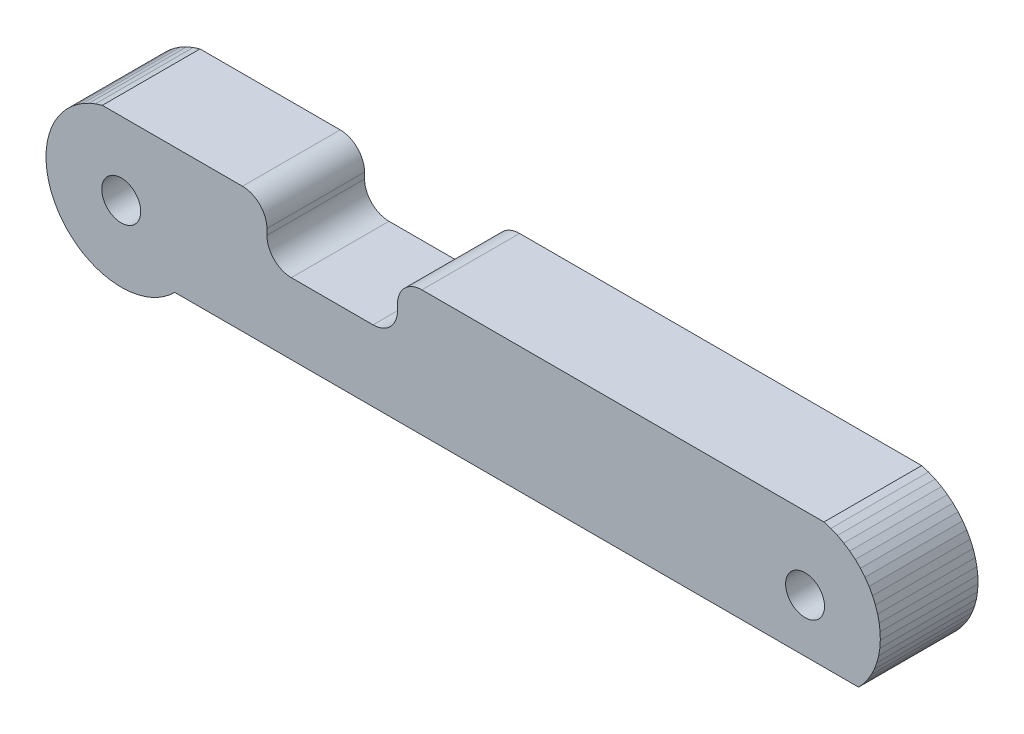
SolidWorks part; units mm, degrees
ref_plane "Front Plane" through (0, 0, 0) normal (0, 0, 1) x (1, 0, 0)
ref_plane "Top Plane" through (0, 0, 0) normal (0, 1, 0) x (1, 0, 0)
ref_plane "Right Plane" through (0, 0, 0) normal (1, 0, 0) x (0, 0, -1)
ref_plane "Plane1" through (0, 0, 0) normal (0, 0, -1) x (-1, 0, 0)
sketch "Sketch1" plane through (0, 0, 0) normal (0, 0, -1) x (-1, 0, 0)
  line L0 (150.2249, 11.5257) -> (149.0942, 12.4373)
  line L1 (149.0942, 12.4373) -> (147.8827, 13.2384)
  line L2 (147.8827, 13.2384) -> (146.6011, 13.9218)
  line L3 (146.6011, 13.9218) -> (145.2609, 14.4815)
  line L4 (145.2609, 14.4815) -> (143.874, 14.9125)
  line L5 (143.874, 14.9125) -> (-3.874, 14.9125)
  line L6 (-3.874, 14.9125) -> (-5.2758, 14.4761)
  line L7 (-5.2758, 14.4761) -> (-6.6297, 13.9082)
  line L8 (-6.6297, 13.9082) -> (-7.9234, 13.2141)
  line L9 (-7.9234, 13.2141) -> (-9.1451, 12.3999)
  line L10 (-9.1451, 12.3999) -> (-10.2838, 11.4732)
  line L11 (-10.2838, 11.4732) -> (-11.3292, 10.4423)
  line L12 (-11.3292, 10.4423) -> (-12.2716, 9.3165)
  line L13 (-12.2716, 9.3165) -> (-13.1027, 8.1062)
  line L14 (-13.1027, 8.1062) -> (-13.8148, 6.8223)
  line L15 (-13.8148, 6.8223) -> (-14.4014, 5.4764)
  line L16 (-14.4014, 5.4764) -> (-14.8573, 4.0808)
  line L17 (-14.8573, 4.0808) -> (-15.1782, 2.6482)
  line L18 (-15.1782, 2.6482) -> (-15.3614, 1.1915)
  line L19 (-15.3614, 1.1915) -> (-15.405, -0.2761)
  line L20 (-15.405, -0.2761) -> (-15.3088, -1.7411)
  line L21 (-15.3088, -1.7411) -> (-15.0736, -3.1903)
  line L22 (-15.0736, -3.1903) -> (-14.7015, -4.6105)
  line L23 (-14.7015, -4.6105) -> (-14.1959, -5.9889)
  line L24 (-14.1959, -5.9889) -> (-13.5614, -7.3129)
  line L25 (-13.5614, -7.3129) -> (-12.8038, -8.5705)
  line L26 (-12.8038, -8.5705) -> (-11.93, -9.7502)
  line L27 (-11.93, -9.7502) -> (-10.9478, -10.8415)
  line L28 (-10.9478, -10.8415) -> (129.0522, -10.8415)
  line L29 (129.0522, -10.8415) -> (130.1217, -11.8242)
  line L30 (130.1217, -11.8242) -> (131.279, -12.7018)
  line L31 (131.279, -12.7018) -> (132.5137, -13.4665)
  line L32 (132.5137, -13.4665) -> (133.815, -14.1116)
  line L33 (133.815, -14.1116) -> (135.1712, -14.6313)
  line L34 (135.1712, -14.6313) -> (136.5704, -15.0209)
  line L35 (136.5704, -15.0209) -> (138, -15.2771)
  line L36 (138, -15.2771) -> (139.4474, -15.3976)
  line L37 (139.4474, -15.3976) -> (140.8997, -15.3812)
  line L38 (140.8997, -15.3812) -> (142.344, -15.2282)
  line L39 (142.344, -15.2282) -> (143.7675, -14.9398)
  line L40 (143.7675, -14.9398) -> (145.1575, -14.5187)
  line L41 (145.1575, -14.5187) -> (146.5016, -13.9685)
  line L42 (146.5016, -13.9685) -> (147.788, -13.2943)
  line L43 (147.788, -13.2943) -> (149.0052, -12.5019)
  line L44 (149.0052, -12.5019) -> (150.1424, -11.5984)
  line L45 (150.1424, -11.5984) -> (151.1894, -10.5919)
  line L46 (151.1894, -10.5919) -> (152.1371, -9.4912)
  line L47 (152.1371, -9.4912) -> (152.9768, -8.3062)
  line L48 (152.9768, -8.3062) -> (153.7013, -7.0474)
  line L49 (153.7013, -7.0474) -> (154.304, -5.726)
  line L50 (154.304, -5.726) -> (154.7796, -4.3536)
  line L51 (154.7796, -4.3536) -> (155.1239, -2.9426)
  line L52 (155.1239, -2.9426) -> (155.3338, -1.5055)
  line L53 (155.3338, -1.5055) -> (155.4074, -0.055)
  line L54 (155.4074, -0.055) -> (155.3441, 1.396)
  line L55 (155.3441, 1.396) -> (155.1445, 2.8347)
  line L56 (155.1445, 2.8347) -> (154.8103, 4.2481)
  line L57 (154.8103, 4.2481) -> (154.3445, 5.6237)
  line L58 (154.3445, 5.6237) -> (153.7512, 6.9494)
  line L59 (153.7512, 6.9494) -> (153.0358, 8.2134)
  line L60 (153.0358, 8.2134) -> (152.2045, 9.4043)
  line L61 (152.2045, 9.4043) -> (151.2647, 10.5117)
  line L62 (151.2647, 10.5117) -> (150.2249, 11.5257)
extrude "Boss-Extrude1" add sketch "Sketch1" against normal blind 20
sketch "Sketch2" plane through (0, 0, 20) normal (0, 0, 1) x (1, 0, 0)
  line L0 (3.7299, 1.445) -> (3.4009, 2.1057)
  line L1 (3.4009, 2.1057) -> (2.956, 2.6948)
  line L2 (2.956, 2.6948) -> (2.4105, 3.1921)
  line L3 (2.4105, 3.1921) -> (1.783, 3.5807)
  line L4 (1.783, 3.5807) -> (1.0947, 3.8473)
  line L5 (1.0947, 3.8473) -> (0.3691, 3.9829)
  line L6 (0.3691, 3.9829) -> (-0.3691, 3.9829)
  line L7 (-0.3691, 3.9829) -> (-1.0947, 3.8473)
  line L8 (-1.0947, 3.8473) -> (-1.783, 3.5807)
  line L9 (-1.783, 3.5807) -> (-2.4105, 3.1921)
  line L10 (-2.4105, 3.1921) -> (-2.956, 2.6948)
  line L11 (-2.956, 2.6948) -> (-3.4009, 2.1057)
  line L12 (-3.4009, 2.1057) -> (-3.7299, 1.445)
  line L13 (-3.7299, 1.445) -> (-3.9319, 0.735)
  line L14 (-3.9319, 0.735) -> (-4, 0)
  line L15 (-4, 0) -> (-3.9319, -0.735)
  line L16 (-3.9319, -0.735) -> (-3.7299, -1.445)
  line L17 (-3.7299, -1.445) -> (-3.4009, -2.1057)
  line L18 (-3.4009, -2.1057) -> (-2.956, -2.6948)
  line L19 (-2.956, -2.6948) -> (-2.4105, -3.1921)
  line L20 (-2.4105, -3.1921) -> (-1.783, -3.5807)
  line L21 (-1.783, -3.5807) -> (-1.0947, -3.8473)
  line L22 (-1.0947, -3.8473) -> (-0.3691, -3.9829)
  line L23 (-0.3691, -3.9829) -> (0.3691, -3.9829)
  line L24 (0.3691, -3.9829) -> (1.0947, -3.8473)
  line L25 (1.0947, -3.8473) -> (1.783, -3.5807)
  line L26 (1.783, -3.5807) -> (2.4105, -3.1921)
  line L27 (2.4105, -3.1921) -> (2.956, -2.6948)
  line L28 (2.956, -2.6948) -> (3.4009, -2.1057)
  line L29 (3.4009, -2.1057) -> (3.7299, -1.445)
  line L30 (3.7299, -1.445) -> (3.9319, -0.735)
  line L31 (3.9319, -0.735) -> (4, 0)
  line L32 (4, 0) -> (3.9319, 0.735)
  line L33 (3.9319, 0.735) -> (3.7299, 1.445)
extrude "Cut-Extrude1" cut sketch "Sketch2" against normal through all
sketch "Sketch3" plane through (0, 0, 20) normal (0, 0, 1) x (1, 0, 0)
  line L0 (-139.6309, 3.9829) -> (-140.3691, 3.9829)
  line L1 (-140.3691, 3.9829) -> (-141.0947, 3.8473)
  line L2 (-141.0947, 3.8473) -> (-141.783, 3.5807)
  line L3 (-141.783, 3.5807) -> (-142.4105, 3.1921)
  line L4 (-142.4105, 3.1921) -> (-142.956, 2.6948)
  line L5 (-142.956, 2.6948) -> (-143.4009, 2.1057)
  line L6 (-143.4009, 2.1057) -> (-143.7299, 1.445)
  line L7 (-143.7299, 1.445) -> (-143.9319, 0.735)
  line L8 (-143.9319, 0.735) -> (-144, 0)
  line L9 (-144, 0) -> (-143.9319, -0.735)
  line L10 (-143.9319, -0.735) -> (-143.7299, -1.445)
  line L11 (-143.7299, -1.445) -> (-143.4009, -2.1057)
  line L12 (-143.4009, -2.1057) -> (-142.956, -2.6948)
  line L13 (-142.956, -2.6948) -> (-142.4105, -3.1921)
  line L14 (-142.4105, -3.1921) -> (-141.783, -3.5807)
  line L15 (-141.783, -3.5807) -> (-141.0947, -3.8473)
  line L16 (-141.0947, -3.8473) -> (-140.3691, -3.9829)
  line L17 (-140.3691, -3.9829) -> (-139.6309, -3.9829)
  line L18 (-139.6309, -3.9829) -> (-138.9053, -3.8473)
  line L19 (-138.9053, -3.8473) -> (-138.217, -3.5807)
  line L20 (-138.217, -3.5807) -> (-137.5895, -3.1921)
  line L21 (-137.5895, -3.1921) -> (-137.044, -2.6948)
  line L22 (-137.044, -2.6948) -> (-136.5991, -2.1057)
  line L23 (-136.5991, -2.1057) -> (-136.2701, -1.445)
  line L24 (-136.2701, -1.445) -> (-136.0681, -0.735)
  line L25 (-136.0681, -0.735) -> (-136, 0)
  line L26 (-136, 0) -> (-136.0681, 0.735)
  line L27 (-136.0681, 0.735) -> (-136.2701, 1.445)
  line L28 (-136.2701, 1.445) -> (-136.5991, 2.1057)
  line L29 (-136.5991, 2.1057) -> (-137.044, 2.6948)
  line L30 (-137.044, 2.6948) -> (-137.5895, 3.1921)
  line L31 (-137.5895, 3.1921) -> (-138.217, 3.5807)
  line L32 (-138.217, 3.5807) -> (-138.9053, 3.8473)
  line L33 (-138.9053, 3.8473) -> (-139.6309, 3.9829)
extrude "Cut-Extrude2" cut sketch "Sketch3" against normal through all
sketch "Sketch4" plane through (0, -10.8415, 0) normal (0, -1, 0) x (1, 0, 0)
  line L0 (1.3314, 10.725) -> (1.1865, 10.3753)
  line L1 (1.1865, 10.3753) -> (1.1371, 10)
  line L2 (1.1371, 10) -> (1.1865, 9.6247)
  line L3 (1.1865, 9.6247) -> (1.3314, 9.275)
  line L4 (1.3314, 9.275) -> (1.5618, 8.9747)
  line L5 (1.5618, 8.9747) -> (1.8621, 8.7443)
  line L6 (1.8621, 8.7443) -> (2.2118, 8.5994)
  line L7 (2.2118, 8.5994) -> (2.5871, 8.55)
  line L8 (2.5871, 8.55) -> (2.9624, 8.5994)
  line L9 (2.9624, 8.5994) -> (3.3121, 8.7443)
  line L10 (3.3121, 8.7443) -> (3.6124, 8.9747)
  line L11 (3.6124, 8.9747) -> (3.8428, 9.275)
  line L12 (3.8428, 9.275) -> (3.9877, 9.6247)
  line L13 (3.9877, 9.6247) -> (4.0371, 10)
  line L14 (4.0371, 10) -> (3.9877, 10.3753)
  line L15 (3.9877, 10.3753) -> (3.8428, 10.725)
  line L16 (3.8428, 10.725) -> (3.6124, 11.0253)
  line L17 (3.6124, 11.0253) -> (3.3121, 11.2557)
  line L18 (3.3121, 11.2557) -> (2.9624, 11.4006)
  line L19 (2.9624, 11.4006) -> (2.5871, 11.45)
  line L20 (2.5871, 11.45) -> (2.2118, 11.4006)
  line L21 (2.2118, 11.4006) -> (1.8621, 11.2557)
  line L22 (1.8621, 11.2557) -> (1.5618, 11.0253)
  line L23 (1.5618, 11.0253) -> (1.3314, 10.725)
sketch "Sketch5" plane through (0, -10.8415, 0) normal (0, -1, 0) x (1, 0, 0)
  line L0 (-42.0428, 10.725) -> (-42.1877, 10.3753)
  line L1 (-42.1877, 10.3753) -> (-42.2371, 10)
  line L2 (-42.2371, 10) -> (-42.1877, 9.6247)
  line L3 (-42.1877, 9.6247) -> (-42.0428, 9.275)
  line L4 (-42.0428, 9.275) -> (-41.8124, 8.9747)
  line L5 (-41.8124, 8.9747) -> (-41.5121, 8.7443)
  line L6 (-41.5121, 8.7443) -> (-41.1624, 8.5994)
  line L7 (-41.1624, 8.5994) -> (-40.7871, 8.55)
  line L8 (-40.7871, 8.55) -> (-40.4118, 8.5994)
  line L9 (-40.4118, 8.5994) -> (-40.0621, 8.7443)
  line L10 (-40.0621, 8.7443) -> (-39.7618, 8.9747)
  line L11 (-39.7618, 8.9747) -> (-39.5314, 9.275)
  line L12 (-39.5314, 9.275) -> (-39.3865, 9.6247)
  line L13 (-39.3865, 9.6247) -> (-39.3371, 10)
  line L14 (-39.3371, 10) -> (-39.3865, 10.3753)
  line L15 (-39.3865, 10.3753) -> (-39.5314, 10.725)
  line L16 (-39.5314, 10.725) -> (-39.7618, 11.0253)
  line L17 (-39.7618, 11.0253) -> (-40.0621, 11.2557)
  line L18 (-40.0621, 11.2557) -> (-40.4118, 11.4006)
  line L19 (-40.4118, 11.4006) -> (-40.7871, 11.45)
  line L20 (-40.7871, 11.45) -> (-41.1624, 11.4006)
  line L21 (-41.1624, 11.4006) -> (-41.5121, 11.2557)
  line L22 (-41.5121, 11.2557) -> (-41.8124, 11.0253)
  line L23 (-41.8124, 11.0253) -> (-42.0428, 10.725)
ref_plane "Plane2" through (0, 0, -10) normal (0, 0, -1) x (-1, 0, 0)
sketch "Sketch6" plane through (0, 0, -10) normal (0, 0, -1) x (-1, 0, 0)
  line L126 (151.2647, 10.6737) -> (150.2249, 11.6877)
  line L127 (150.2249, 11.6877) -> (149.0942, 12.5993)
  line L128 (149.0942, 12.5993) -> (147.8827, 13.4004)
  line L129 (147.8827, 13.4004) -> (146.6011, 14.0838)
  line L130 (146.6011, 14.0838) -> (145.2609, 14.6435)
  line L131 (145.2609, 14.6435) -> (143.874, 15.0745)
  line L132 (143.874, 15.0745) -> (-3.874, 15.0745)
  line L133 (-3.874, 15.0745) -> (-5.2758, 14.6381)
  line L134 (-5.2758, 14.6381) -> (-6.6297, 14.0702)
  line L135 (-6.6297, 14.0702) -> (-7.9234, 13.376)
  line L136 (-7.9234, 13.376) -> (-9.1451, 12.5619)
  line L137 (-9.1451, 12.5619) -> (-10.2838, 11.6352)
  line L138 (-10.2838, 11.6352) -> (-11.3292, 10.6043)
  line L139 (-11.3292, 10.6043) -> (-12.2716, 9.4785)
  line L140 (-12.2716, 9.4785) -> (-13.1027, 8.2682)
  line L141 (-13.1027, 8.2682) -> (-13.8148, 6.9843)
  line L142 (-13.8148, 6.9843) -> (-14.4014, 5.6384)
  line L143 (-14.4014, 5.6384) -> (-14.8573, 4.2428)
  line L144 (-14.8573, 4.2428) -> (-15.1782, 2.8101)
  line L145 (-15.1782, 2.8101) -> (-15.3614, 1.3534)
  line L146 (-15.3614, 1.3534) -> (-15.405, -0.1141)
  line L147 (-15.405, -0.1141) -> (-15.3088, -1.5791)
  line L148 (-15.3088, -1.5791) -> (-15.0736, -3.0283)
  line L149 (-15.0736, -3.0283) -> (-14.7015, -4.4485)
  line L150 (-14.7015, -4.4485) -> (-14.1959, -5.8269)
  line L151 (-14.1959, -5.8269) -> (-13.5614, -7.1509)
  line L152 (-13.5614, -7.1509) -> (-12.8038, -8.4085)
  line L153 (-12.8038, -8.4085) -> (-11.93, -9.5882)
  line L154 (-11.93, -9.5882) -> (-10.9478, -10.6795)
  line L155 (-10.9478, -10.6795) -> (129.0522, -10.6795)
  line L156 (129.0522, -10.6795) -> (130.1217, -11.6622)
  line L157 (130.1217, -11.6622) -> (131.279, -12.5398)
  line L158 (131.279, -12.5398) -> (132.5137, -13.3045)
  line L159 (132.5137, -13.3045) -> (133.815, -13.9496)
  line L160 (133.815, -13.9496) -> (135.1712, -14.4693)
  line L161 (135.1712, -14.4693) -> (136.5704, -14.859)
  line L162 (136.5704, -14.859) -> (138, -15.1152)
  line L163 (138, -15.1152) -> (139.4474, -15.2356)
  line L164 (139.4474, -15.2356) -> (140.8997, -15.2192)
  line L165 (140.8997, -15.2192) -> (142.344, -15.0662)
  line L166 (142.344, -15.0662) -> (143.7675, -14.7778)
  line L167 (143.7675, -14.7778) -> (145.1575, -14.3567)
  line L168 (145.1575, -14.3567) -> (146.5016, -13.8065)
  line L169 (146.5016, -13.8065) -> (147.788, -13.1323)
  line L170 (147.788, -13.1323) -> (149.0052, -12.3399)
  line L171 (149.0052, -12.3399) -> (150.1424, -11.4364)
  line L172 (150.1424, -11.4364) -> (151.1894, -10.4299)
  line L173 (151.1894, -10.4299) -> (152.1371, -9.3292)
  line L174 (152.1371, -9.3292) -> (152.9768, -8.1442)
  line L175 (152.9768, -8.1442) -> (153.7013, -6.8854)
  line L176 (153.7013, -6.8854) -> (154.304, -5.564)
  line L177 (154.304, -5.564) -> (154.7796, -4.1917)
  line L178 (154.7796, -4.1917) -> (155.1239, -2.7807)
  line L179 (155.1239, -2.7807) -> (155.3338, -1.3435)
  line L180 (155.3338, -1.3435) -> (155.4074, 0.107)
  line L181 (155.4074, 0.107) -> (155.3441, 1.558)
  line L182 (155.3441, 1.558) -> (155.1445, 2.9966)
  line L183 (155.1445, 2.9966) -> (154.8103, 4.4101)
  line L184 (154.8103, 4.4101) -> (154.3445, 5.7857)
  line L185 (154.3445, 5.7857) -> (153.7512, 7.1114)
  line L186 (153.7512, 7.1114) -> (153.0358, 8.3754)
  line L187 (153.0358, 8.3754) -> (152.2045, 9.5663)
  line L188 (152.2045, 9.5663) -> (151.2647, 10.6737)
  circle A0 centre (0, 0) radius 3.9829
  circle A1 centre (140.0068, -0.0089) radius 3.9905
ref_plane "Plane3" through (0, 0, 20) normal (0, 0, 1) x (1, 0, 0)
sketch "Sketch7" plane through (0, 0, 20) normal (0, 0, 1) x (1, 0, 0)
  line L1 (-147.5796, 5.778) -> (-131.7543, 5.778)
  line L2 (-147.5796, 5.778) -> (-147.5796, -6.435)
  line L3 (-147.5796, -6.435) -> (-131.7543, -6.435)
  line L4 (-131.7543, 5.778) -> (-131.7543, -6.435)
  line L5 (-5.0827, 4.2322) -> (5.4063, 4.2322)
  line L6 (-5.0827, 4.2322) -> (-5.0827, -4.2285)
  line L7 (-5.0827, -4.2285) -> (5.4063, -4.2285)
  line L8 (5.4063, 4.2322) -> (5.4063, -4.2285)
extrude "Boss-Extrude5" add sketch "Sketch7" against normal blind 20
extrude "Cut-Extrude8" cut sketch "Sketch6" against normal blind 40 contours A0 | A1
sketch "Sketch8" plane through (0, 0, 20) normal (0, 0, 1) x (1, 0, 0)
  line L0 (-143.874, 14.9125) -> (3.874, 14.9125) construction
  line L1 (-83.4461, 14.9125) -> (-110.1805, 14.9125)
  line L2 (-83.4461, 14.9125) -> (-83.4461, 3.7017)
  line L3 (-83.4461, 3.7017) -> (-110.1805, 3.7017)
  line L4 (-110.1805, 14.9125) -> (-110.1805, 3.7017)
  line L5 (-83.5177, 3.5341) -> (-83.1429, 63.1605) construction
extrude "Cut-Extrude9" cut sketch "Sketch8" against normal blind 30
fillet "Fillet1" radius 5 2 edges at (-83.4461, 3.7017, 10) (-110.1805, 3.7017, 10)
fillet "Fillet2" radius 5 2 edges at (-83.4461, 14.9125, 10) (-110.1805, 14.9125, 10)
sketch "Sketch9" plane through (0, 2.5492, 0) normal (0, 0, -1) x (-1, 0, 0)
  line L0 (6.3747, 5.0663) -> (6.3747, -6.6682)
  line L1 (6.3747, -6.6682) -> (73.7497, -6.6682)
  line L2 (73.7497, -6.6682) -> (73.7497, 5.0663)
  line L3 (73.7497, 5.0663) -> (6.3747, 5.0663)
extrude "Cut-Extrude10" cut sketch "Sketch9" against normal blind 8
sketch "Sketch11" plane through (-612.7486, 40.8415, -774.3823) normal (0, 1, 0) x (1, 0, 0)
  circle A0 centre (612.3803, -785.4221) radius 1.524
